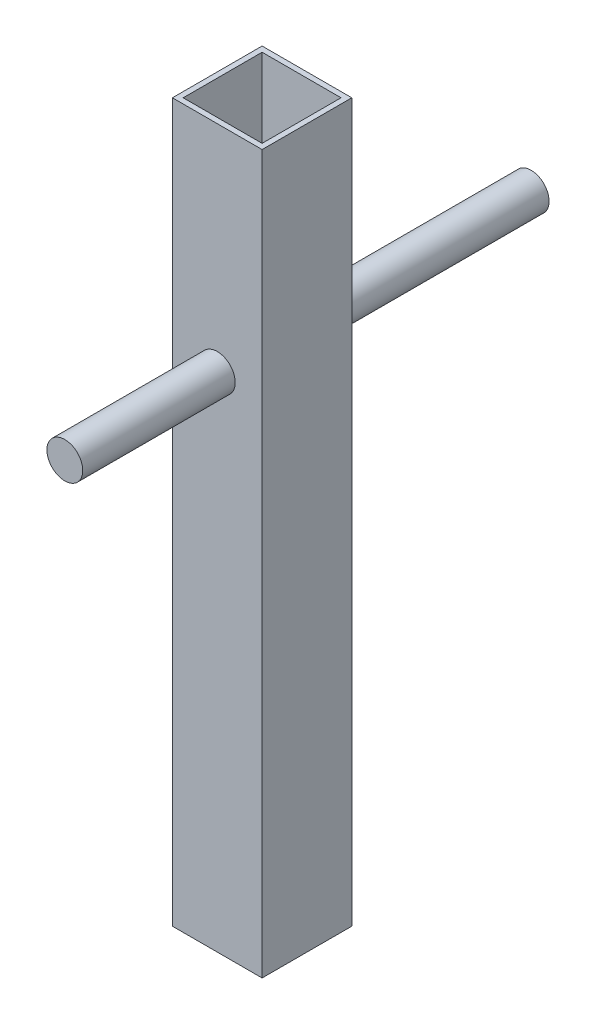
SolidWorks part; units mm, degrees
ref_plane "Front Plane" through (0, 0, 0) normal (0, 0, 1) x (1, 0, 0)
ref_plane "Top Plane" through (0, 0, 0) normal (0, 1, 0) x (1, 0, 0)
ref_plane "Right Plane" through (0, 0, 0) normal (1, 0, 0) x (0, 0, -1)
sketch "Sketch3" plane through (0, 0, 0) normal (0, 1, 0) x (1, 0, 0)
  line L0 (0, 86.7063) -> (0, -87.1032) construction
  line L1 (-136.9048, 0) -> (130.9524, 0) construction
  line L7 (-12.5, 12.5) -> (12.5, 12.5)
  line L8 (-12.5, 12.5) -> (-12.5, -12.5)
  line L13 (-12.5, -12.5) -> (12.5, -12.5)
  line L14 (12.5, 12.5) -> (12.5, -12.5)
  line L15 (-12.5, 12.5) -> (12.5, -12.5) construction
  line L16 (-12.5, -12.5) -> (12.5, 12.5) construction
  line L17 (-11, 11) -> (11, 11)
  line L18 (-11, 11) -> (-11, -11)
  line L19 (-11, -11) -> (11, -11)
  line L20 (11, 11) -> (11, -11)
  line L21 (-11, 11) -> (11, -11) construction
  line L22 (-11, -11) -> (11, 11) construction
  point P5 (0, 0)
  point P10 (0, 0)
  dimension "D1" = 25
  dimension "D2" = 25
  dimension "D3" = 22
extrude "Boss-Extrude1" add sketch "Sketch3" along normal blind 200
sketch "Sketch4" plane through (0, 0, 12.5) normal (0, 0, 1) x (1, 0, 0)
  line L0 (-12.5, 200) -> (12.5, 200) construction
  line L2 (12.5, 200) -> (12.5, 0) construction
  circle A0 centre (0, 140) radius 5
  point P6 (12.5, 146.6306)
  dimension "D1" = 10
  dimension "D2" = 60
  dimension "D3" = 12.5
extrude "Cut-Extrude1" cut sketch "Sketch4" against normal blind 25
sketch "Sketch5" plane through (0, 0, 0) normal (0, 0, 1) x (1, 0, 0)
  circle A0 centre (0, 140) radius 5
extrude "Boss-Extrude2" add sketch "Sketch5" along normal blind 55 and the other way blind 75
